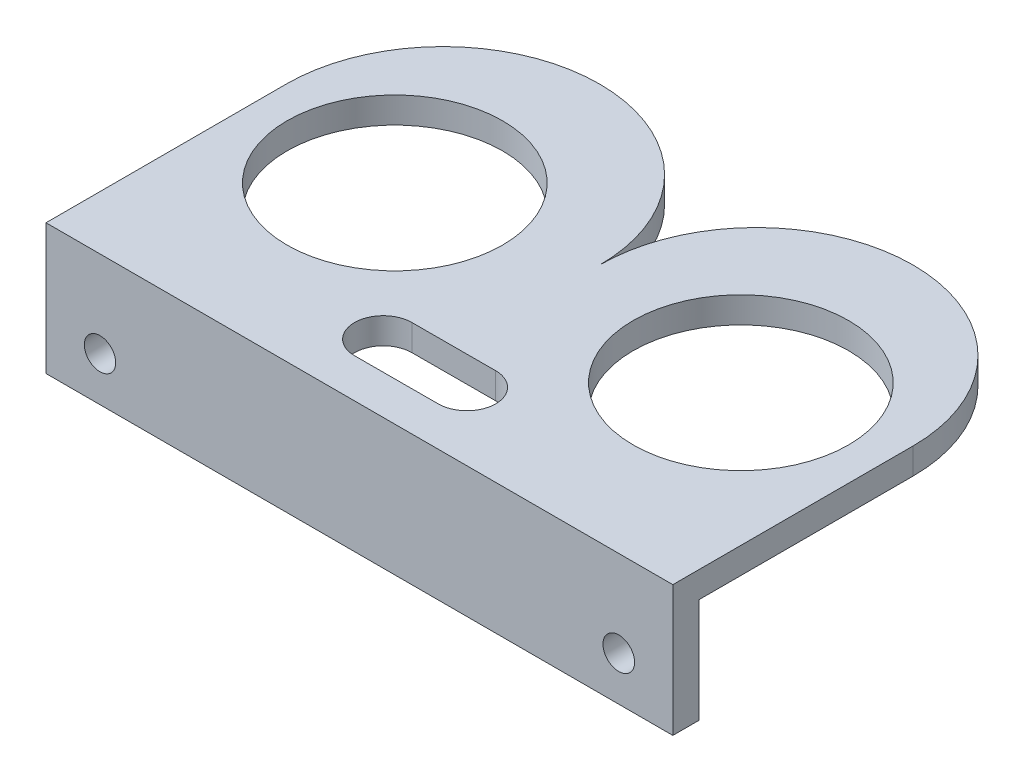
SolidWorks part; units mm, degrees
ref_plane "Front Plane" through (0, 0, 0) normal (0, 0, 1) x (1, 0, 0)
ref_plane "Top Plane" through (0, 0, 0) normal (0, 1, 0) x (1, 0, 0)
ref_plane "Right Plane" through (0, 0, 0) normal (1, 0, 0) x (0, 0, -1)
sketch "Sketch1" plane through (0, 0, 0) normal (0, 0, 1) x (1, 0, 0)
  line L1 (-24, 5) -> (24, 5)
  line L2 (-24, 5) -> (-24, -5)
  line L3 (-24, -5) -> (24, -5)
  line L4 (24, 5) -> (24, -5)
  line L5 (-24, 5) -> (24, -5) construction
  line L6 (-24, -5) -> (24, 5) construction
  point P0 (0, 0)
  dimension "D1" = 48
  dimension "D2" = 10
extrude "Boss-Extrude5" add sketch "Sketch1" against normal blind 2
sketch "Sketch2" plane through (0, 0, 0) normal (0, 1, 0) x (1, 0, 0)
  line L0 (-24, 2) -> (24, 2) construction
  line L1 (-22.759, 23.7121) -> (22.759, 23.7121)
  line L2 (-24, 18.3976) -> (-24, 2)
  line L3 (-24, 2) -> (24, 2)
  line L4 (24, 18.3976) -> (24, 2)
  line L5 (-22.4674, 24.2656) -> (24, 2) construction
  line L6 (-24, 2) -> (22.4674, 24.2656) construction
  line L8 (-24, 2) -> (-24, 0) construction
  circle A0 centre (-12, 18.3976) radius 12
  circle A1 centre (12, 18.3976) radius 12
  point P0 (0, 13.5)
extrude "Boss-Extrude6" add sketch "Sketch2" against normal blind 2 from surface at 5 contours L1 A0 | L1 A0 | A1 L1 | L1 A1 | A1 A0 L2 L3 L4 starting at face at (0, 5, -1)
sketch "Sketch3" plane through (0, 5, 0) normal (0, 1, 0) x (1, 0, 0)
  circle A0 centre (-13.2865, 15.9965) radius 8.25
  circle A1 centre (13.2135, 15.9965) radius 8.25
  dimension "D1" = 26.5
extrude "Cut-Extrude1" cut sketch "Sketch3" against normal blind 2 contours A0 | A1
sketch "Sketch5" plane through (0, 0, 0) normal (0, 1, 0) x (1, 0, 0)
  line L0 (-3.3736, 7.3939) -> (3.0264, 7.4061)
  line L1 (-3.3652, 2.9939) -> (3.0347, 3.0061)
  line L2 (24, 0) -> (-24, 0) construction
  arc A4 (-3.3736, 7.3939) -> (-3.3652, 2.9939) centre (-3.3694, 5.1939) ccw
  arc A6 (3.0264, 7.4061) -> (3.0347, 3.0061) centre (3.0306, 5.2061) cw
  point P4 (-0.1653, 3)
  dimension "D2" = 3
extrude "Cut-Extrude2" cut sketch "Sketch5" against normal through all both and the other way through all
sketch "Sketch6" plane through (0, 0, 0) normal (0, 0, 1) x (1, 0, 0)
  line L3 (-24, 5) -> (-24, -5) construction
  line L4 (24, -5) -> (24, 5) construction
  circle A0 centre (-19.8646, -1.6166) radius 1.2
  circle A1 centre (19.86, -1.6166) radius 1.2119
  dimension "D1" = 4.1354
  dimension "D2" = 4.14
extrude "Cut-Extrude3" cut sketch "Sketch6" against normal blind 10 and the other way through all
